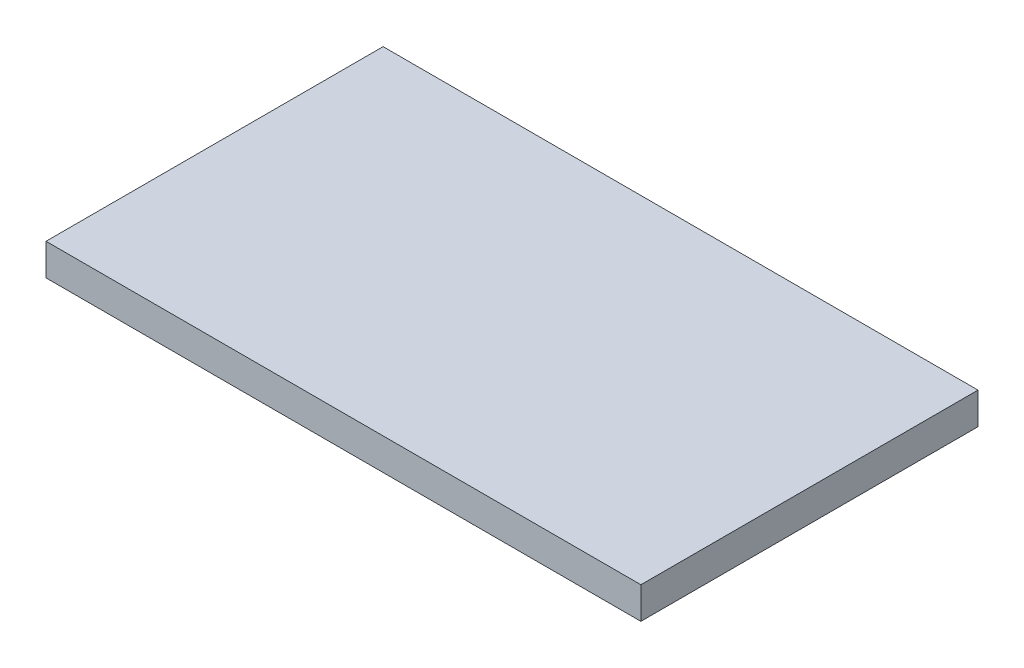
SolidWorks part; units mm, degrees
material "Клен"
ref_plane "Спереди (XY)" through (0, 0, 0) normal (0, 0, 1) x (1, 0, 0)
ref_plane "Сверху (XZ)" through (0, 0, 0) normal (0, 1, 0) x (1, 0, 0)
ref_plane "Справа (ZY)" through (0, 0, 0) normal (1, 0, 0) x (0, 0, -1)
sketch "Эскиз1" plane through (0, 0, 0) normal (0, 1, 0) x (1, 0, 0)
  line L1 (75, -42.5) -> (-75, -42.5)
  line L2 (75, -42.5) -> (75, 42.5)
  line L3 (75, 42.5) -> (-75, 42.5)
  line L4 (-75, -42.5) -> (-75, 42.5)
  line L5 (75, -42.5) -> (-75, 42.5) construction
  line L6 (75, 42.5) -> (-75, -42.5) construction
  point P0 (0, 0)
  dimension "D1" = 150
  dimension "D2" = 85
extrude "Бобышка-Вытянуть1" add sketch "Эскиз1" along normal blind 8
